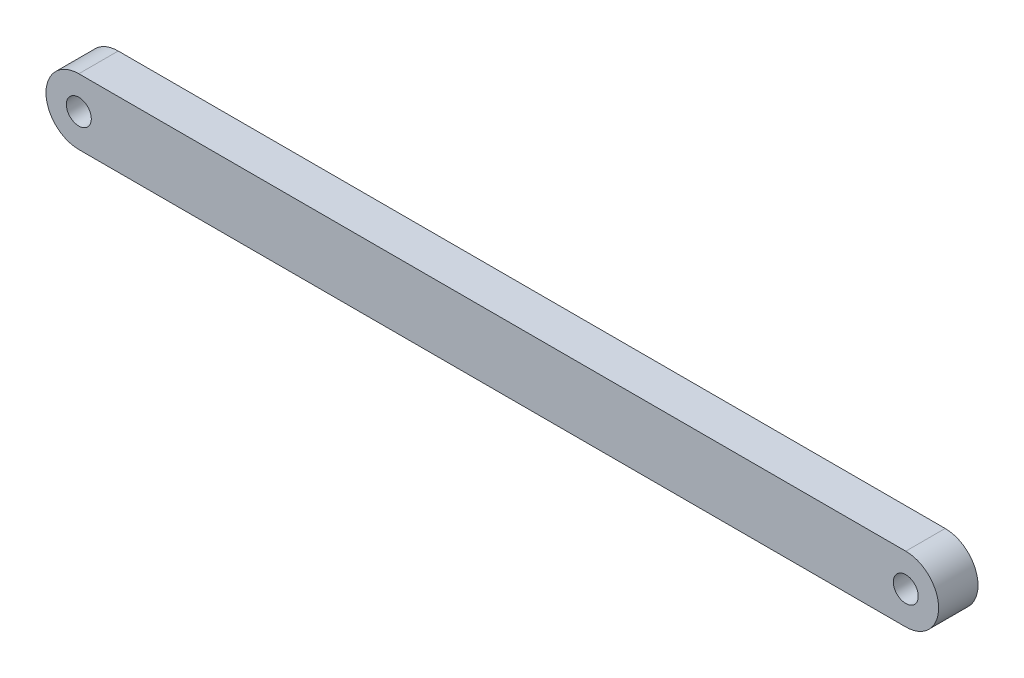
SolidWorks part; units mm, degrees
material "MDF"
ref_plane "Front Plane" through (0, 0, 0) normal (0, 0, 1) x (1, 0, 0)
ref_plane "Top Plane" through (0, 0, 0) normal (0, 1, 0) x (1, 0, 0)
ref_plane "Right Plane" through (0, 0, 0) normal (1, 0, 0) x (0, 0, -1)
sketch "Sketch1" plane through (0, 0, 0) normal (0, 0, 1) x (1, 0, 0)
  line L0 (0, -5) -> (0, 5) construction
  line L1 (-62.9741, 5) -> (62.9741, 5)
  line L2 (-62.9741, -5) -> (62.9741, -5)
  line L3 (62.9741, 0) -> (-62.9741, 0) construction
  arc A0 (62.9741, 5) -> (62.9741, -5) centre (62.9741, 0) cw
  arc A1 (-62.9741, 5) -> (-62.9741, -5) centre (-62.9741, 0) ccw
  circle A2 centre (-62.9741, 0) radius 1.9
  circle A3 centre (62.9741, 0) radius 1.9
  point P4 (0, 0)
  point P8 (0, 5)
  point P11 (0, -5)
  point P13 (0, 0)
  dimension "D3" = 3.8
  dimension "D4" = 3.8
  dimension "D1" = 10
  dimension "D2" = 125.9481
extrude "Boss-Extrude1" add sketch "Sketch1" along normal blind 6
sketch "Sketch2" plane through (0, 0, 6) normal (0, 0, 1) x (1, 0, 0)
  line L0 (25, 0) -> (-25, 0) construction
  line L2 (-45, -2.5) -> (-5, -2.5)
  line L3 (-45, -2.5) -> (-45, 2.5)
  line L4 (-45, 2.5) -> (-5, 2.5)
  line L5 (-5, -2.5) -> (-5, 2.5)
  line L6 (-45, -2.5) -> (-5, 2.5) construction
  line L7 (-45, 2.5) -> (-5, -2.5) construction
  line L8 (5, -2.5) -> (45, -2.5)
  line L9 (5, -2.5) -> (5, 2.5)
  line L10 (5, 2.5) -> (45, 2.5)
  line L11 (45, -2.5) -> (45, 2.5)
  line L12 (5, -2.5) -> (45, 2.5) construction
  line L13 (5, 2.5) -> (45, -2.5) construction
  point P4 (0, 0)
  dimension "D1" = 5
  dimension "D2" = 5
  dimension "D3" = 50
  dimension "D4" = 40
  dimension "D5" = 40
extrude "Cut-Extrude1" [suppressed] cut sketch "Sketch2" against normal through all
